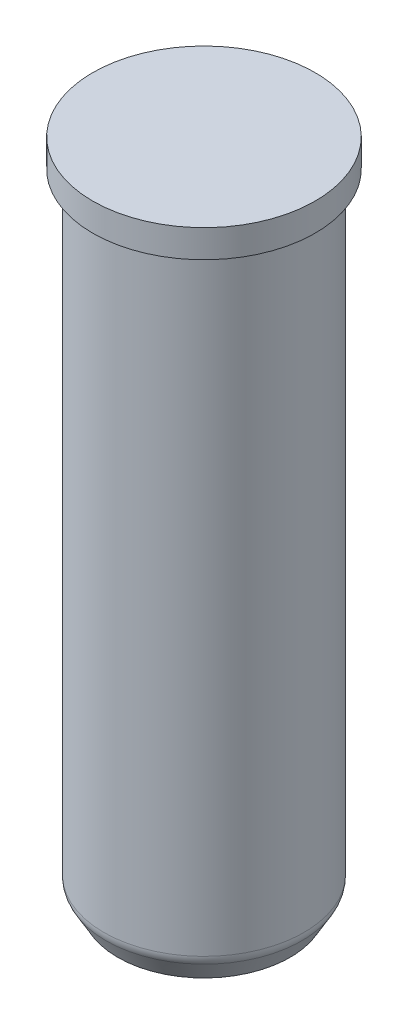
SolidWorks part; units mm, degrees
ref_plane "Front Plane" through (0, 0, 0) normal (0, 0, 1) x (1, 0, 0)
ref_plane "Top Plane" through (0, 0, 0) normal (0, 1, 0) x (1, 0, 0)
ref_plane "Right Plane" through (0, 0, 0) normal (1, 0, 0) x (0, 0, -1)
sketch "Sketch1" plane through (0, 0, 0) normal (0, 1, 0) x (1, 0, 0)
  circle A0 centre (0, 0) radius 1.8
  circle A1 centre (0, 0) radius 1
  dimension "D1" = 3.6
  dimension "D2" = 0.8
extrude "Boss-Extrude1" add sketch "Sketch1" along normal blind 11.5
sketch "Sketch2" plane through (0, 11.5, 0) normal (0, 1, 0) x (1, 0, 0)
  circle A0 centre (0, 0) radius 2
  circle A1 centre (0, 0) radius 1.8 construction
  dimension "D1" = 0.2
extrude "Boss-Extrude2" add sketch "Sketch2" along normal blind 0.5
chamfer "Chamfer1" distance 0.25 angle 60 1 edges at (0, 0, 1.8)
fillet "Fillet1" radius 0.3 1 edges at (0, 0.433, 1.8)
